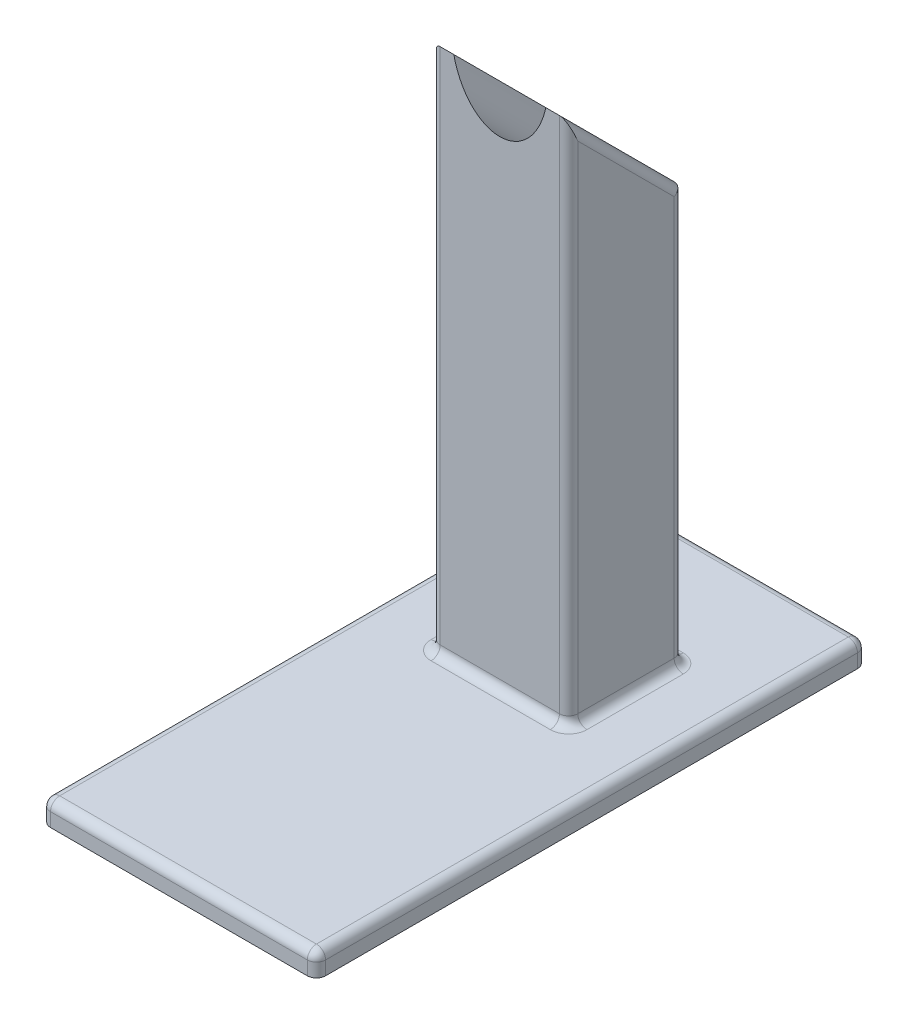
SolidWorks part; units mm, degrees
material "ABS"
ref_plane "Front Plane" through (0, 0, 0) normal (0, 0, 1) x (1, 0, 0)
ref_plane "Top Plane" through (0, 0, 0) normal (0, 1, 0) x (1, 0, 0)
ref_plane "Right Plane" through (0, 0, 0) normal (1, 0, 0) x (0, 0, -1)
sketch "Sketch1" plane through (0, 0, 0) normal (0, 1, 0) x (1, 0, 0)
  line L1 (-38.1, -76.2) -> (38.1, -76.2)
  line L2 (-38.1, -76.2) -> (-38.1, 76.2)
  line L3 (-38.1, 76.2) -> (38.1, 76.2)
  line L4 (38.1, -76.2) -> (38.1, 76.2)
  line L5 (-38.1, -76.2) -> (38.1, 76.2) construction
  line L6 (-38.1, 76.2) -> (38.1, -76.2) construction
  point P0 (0, 0)
  dimension "D1" = 152.4
  dimension "D2" = 76.2
extrude "Boss-Extrude1" add sketch "Sketch1" along normal blind 6.35
sketch "Sketch3" plane through (0, 0, 0) normal (1, 0, 0) x (0, 0, -1)
  line L0 (12.7, 6.35) -> (12.7, 152.4)
  line L1 (-76.2, 6.35) -> (76.2, 6.35) construction
  line L2 (12.7, 152.4) -> (44.45, 120.65)
  line L3 (44.45, 120.65) -> (44.45, 6.35)
  line L4 (76.2, 6.35) -> (76.2, 0) construction
  line L5 (12.7, 6.35) -> (44.45, 6.35)
  dimension "D1" = 45
  dimension "D2" = 31.75
  dimension "D3" = 114.3
  dimension "D4" = 31.75
extrude "Boss-Extrude2" add sketch "Sketch3" along normal blind 19.05 and the other way blind 19.05 contours L0 L2 L3 L5
sketch3d "3DSketch1" plane through (0, 0, 0) normal (0, 0, 1) x (1, 0, 0)
sketch "Sketch4" plane through (0, 0, 0) normal (0, 0.7071, 0.7071) x (1, 0, 0)
  line L0 (0, 0) -> (0, 120.65) construction
  circle A0 centre (0, 120.65) radius 13.335
  dimension "D1" = 26.67
  dimension "D2" = 120.65
extrude "Cut-Extrude1" cut sketch "Sketch4" along normal through all
fillet "Fillet1" radius 2.54 18 edges at (0, 6.35, 76.2) (-38.1, 6.35, 0) (0, 6.35, -76.2) (38.1, 6.35, 0) (19.05, 6.35, -28.575) (0, 6.35, -44.45) (-19.05, 6.35, -28.575) (0, 6.35, -12.7) (19.05, 136.525, -28.575) (-19.05, 136.525, -28.575) (19.05, 63.5, -44.45) (19.05, 79.375, -12.7) (-19.05, 63.5, -44.45) (-19.05, 79.375, -12.7) (-38.1, 3.175, 76.2) (-38.1, 3.175, -76.2) (38.1, 3.175, -76.2) (38.1, 3.175, 76.2)
